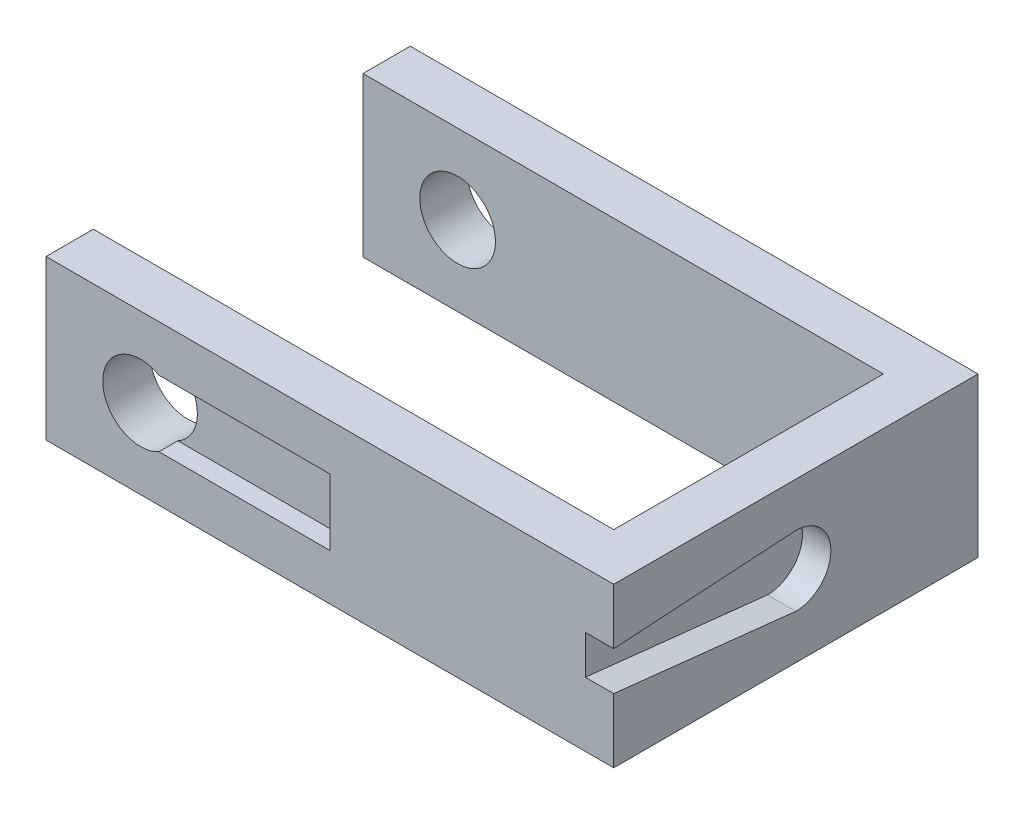
SolidWorks part; units mm, degrees
ref_plane "Front Plane" through (0, 0, 0) normal (0, 0, 1) x (1, 0, 0)
ref_plane "Top Plane" through (0, 0, 0) normal (0, 1, 0) x (1, 0, 0)
ref_plane "Right Plane" through (0, 0, 0) normal (1, 0, 0) x (0, 0, -1)
sketch "Sketch1" plane through (0, 0, 0) normal (0, 1, 0) x (1, 0, 0)
  line L0 (-2.5, 14.25) -> (-2.5, -0.75)
  line L1 (2.5, -14.25) -> (-2.5, -14.25)
  line L2 (2.5, -14.25) -> (2.5, 14.25)
  line L3 (2.5, 14.25) -> (-2.5, 14.25)
  line L4 (-2.5, -14.25) -> (-2.5, 14.25)
  line L5 (2.5, -14.25) -> (-2.5, 14.25) construction
  line L6 (2.5, 14.25) -> (-2.5, -14.25) construction
  line L7 (2.5, 14.25) -> (-57.5, 14.25)
  line L8 (2.5, 14.25) -> (2.5, 19.25)
  line L9 (-57.5, 14.25) -> (-57.5, 19.25)
  line L10 (0, 0) -> (-57.5, 0) construction
  line L11 (2.5, 19.25) -> (-57.5, 19.25)
  line L12 (2.5, -14.25) -> (2.5, -19.25)
  line L13 (-57.5, -14.25) -> (-57.5, -19.25)
  line L14 (2.5, -19.25) -> (-57.5, -19.25)
  line L15 (2.5, -14.25) -> (-57.5, -14.25)
  line L16 (2.5, 0) -> (-57.5, 0) construction
  point P0 (0, 0)
  dimension "D1" = 28.5
  dimension "D2" = 5
  dimension "D3" = 60
  dimension "D4" = 5
extrude "Boss-Extrude2" add sketch "Sketch1" against normal blind 16.8 contours L1 L15 L13 L14 L12 | L4 L1 L2 L3 L0 | L8 L11 L9 L7 L3
sketch "Sketch5" plane through (0, 0, 19.25) normal (0, 0, 1) x (1, 0, 0)
  line L0 (-57.5, -8.4) -> (2.5, -8.4) construction
  line L1 (-57.5, -16.8) -> (-57.5, 0) construction
  line L2 (2.5, -16.8) -> (2.5, 0) construction
  circle A0 centre (-47.5, -8.4) radius 4
  dimension "D1" = 8
  dimension "D2" = 10
extrude "Cut-Extrude3" cut sketch "Sketch5" against normal blind 38.5
sketch "Sketch6" plane through (0, 0, 19.25) normal (0, 0, 1) x (1, 0, 0)
  line L0 (-57.5, -16.8) -> (-57.5, 0) construction
  line L1 (-27.5, -11.9) -> (-47.5, -11.9)
  line L2 (-27.5, -11.9) -> (-27.5, -4.9)
  line L3 (-27.5, -4.9) -> (-47.5, -4.9)
  line L4 (-47.5, -11.9) -> (-47.5, -4.9)
  line L5 (-27.5, -11.9) -> (-47.5, -4.9) construction
  line L6 (-27.5, -4.9) -> (-47.5, -11.9) construction
  circle A0 centre (-47.5, -8.4) radius 4 construction
  point P0 (-37.5, -8.4)
  point P7 (-57.5, -8.4)
  dimension "D1" = 0
  dimension "D2" = 7
  dimension "D3" = 20
  dimension "D4" = 0
extrude "Cut-Extrude4" cut sketch "Sketch6" against normal blind 2
sketch "Sketch8" plane through (0, 0, -19.25) normal (0, 0, -1) x (-1, 0, 0)
  line L0 (47.5, -11.993) -> (27.5, -11.993)
  line L1 (47.5, -11.993) -> (47.5, -4.993)
  line L2 (47.5, -4.993) -> (27.5, -4.993)
  line L3 (27.5, -11.993) -> (27.5, -4.993)
  line L4 (47.5, -11.993) -> (27.5, -4.993) construction
  line L5 (47.5, -4.993) -> (27.5, -11.993) construction
  line L8 (-2.5, -16.8) -> (57.5, -16.8) construction
  circle A0 centre (47.5, -8.4) radius 4 construction
  point P0 (37.5, -8.493)
  dimension "D1" = 7
  dimension "D2" = 20
  dimension "D3" = 11.807
  dimension "D4" = 0
extrude "Cut-Extrude5" cut sketch "Sketch8" against normal blind 2
sketch "Sketch9" plane through (2.5, 0, 0) normal (1, 0, 0) x (0, 0, -1)
  line L4 (19.25, -16.8) -> (-19.25, -16.8) construction
  line L5 (19.25, -16.8) -> (19.25, 0) construction
  line L16 (0, -12.1) -> (-19.25, -10.011)
  line L17 (-19.25, -16.8) -> (-19.25, 0) construction
  line L18 (-19.25, -10.011) -> (-19.25, -5.9)
  line L19 (-19.25, -5.9) -> (0, -4.7)
  circle A0 centre (0, -8.4) radius 3.7
  line M6 (-19.25, 0) -> (-19.25, -16.8)
  dimension "D1" = 8.4
  dimension "D2" = 7.4
  dimension "D3" = 19.25
  dimension "D4" = 5.9
  dimension "D5" = 6.789
extrude "Cut-Extrude8" cut sketch "Sketch9" against normal blind 3 contours A0 L19 L16 M6 | L19 A0 L16
